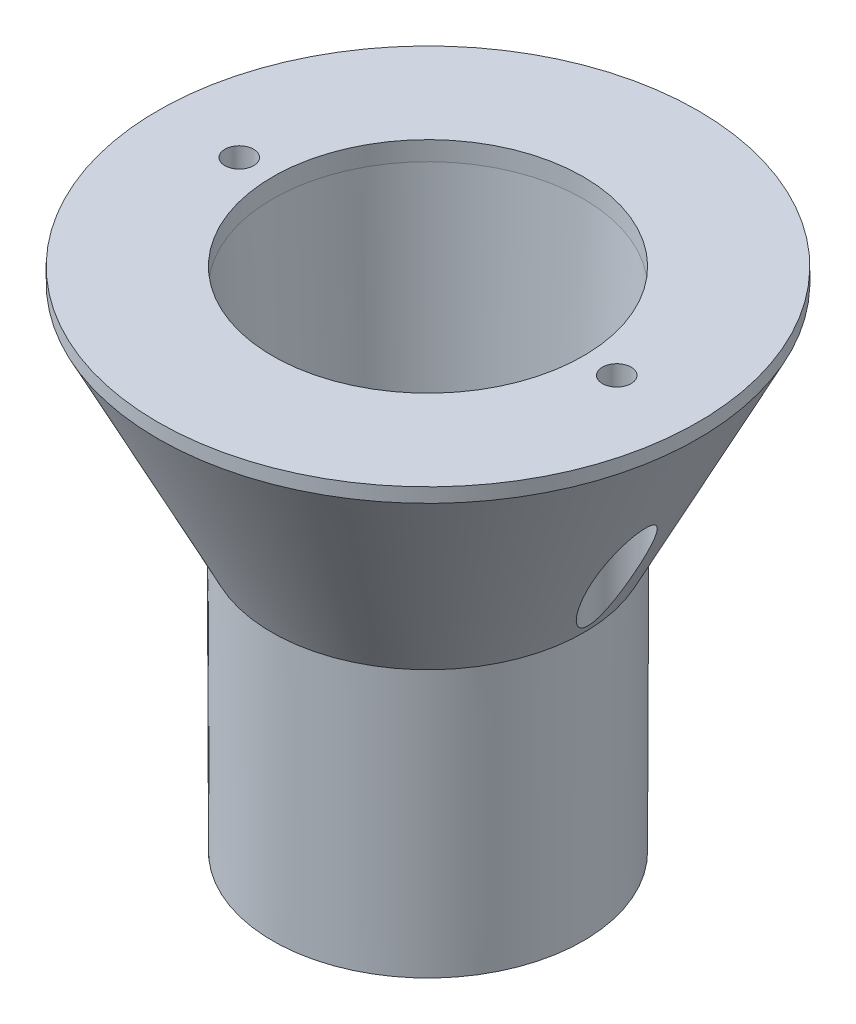
SolidWorks part; units mm, degrees
ref_plane "Спереди" through (0, 0, 0) normal (0, 0, 1) x (1, 0, 0)
ref_plane "Сверху" through (0, 0, 0) normal (0, 1, 0) x (1, 0, 0)
ref_plane "Справа" through (0, 0, 0) normal (1, 0, 0) x (0, 0, -1)
sketch "Эскиз1" plane through (0, 0, 0) normal (0, 0, 1) x (1, 0, 0)
  line L0 (0, 0) -> (0, 106) construction
  line L1 (30, 0) -> (32.5, 0)
  line L2 (32.5, 0) -> (32.6793, 56)
  line L4 (32.5, 106) -> (32.5, 102)
  line L6 (30.1598, 49.924) -> (30, 0)
  line L10 (32.5, 106) -> (56.5, 106)
  line L11 (0, 106) -> (32.5, 106) construction
  line L12 (56.5, 106) -> (56.5, 103)
  line L13 (0, 0) -> (30, 0) construction
  line L14 (56.5, 103) -> (32.6793, 56)
  line L16 (32.5, 102) -> (30.1598, 49.924)
  point P3 (32.5228, 7.1235)
  point P15 (38.1892, 106)
  dimension "D1" = 106
  dimension "D2" = 113
  dimension "D3" = 60
  dimension "D4" = 2.5
  dimension "D5" = 65
  dimension "D6" = 4
  dimension "D7" = 50
  dimension "D9" = 3
revolve "Повернуть2" add sketch "Эскиз1" angle 360 about L0
sketch "Эскиз2" plane through (0, 106, 0) normal (0, 1, 0) x (1, 0, 0)
  line L0 (0, 0) -> (-83.8387, 0) construction
  circle A0 centre (0, 0) radius 39.5 construction
  circle A1 centre (-39.5, 0) radius 3
  dimension "D1" = 79
  dimension "D2" = 6
extrude "Вырез-Вытянуть3" cut sketch "Эскиз2" against normal blind 35
mirror "Зеркальное отражение1" about plane through (0, 0, 0) normal (1, 0, 0) of "Вырез-Вытянуть3"
ref_plane "Плоскость1" through (0, 56, 0) normal (0, 1, 0) x (1, 0, 0)
sketch "Эскиз4" plane through (0, 56, 0) normal (0, 1, 0) x (1, 0, 0)
  circle A0 centre (39.5, 0) radius 6
  dimension "D1" = 12
extrude "Вырез-Вытянуть4" cut sketch "Эскиз4" along normal blind 42 and the other way blind 10
mirror "Зеркальное отражение2" about plane through (0, 0, 0) normal (1, 0, 0) of "Вырез-Вытянуть4"
